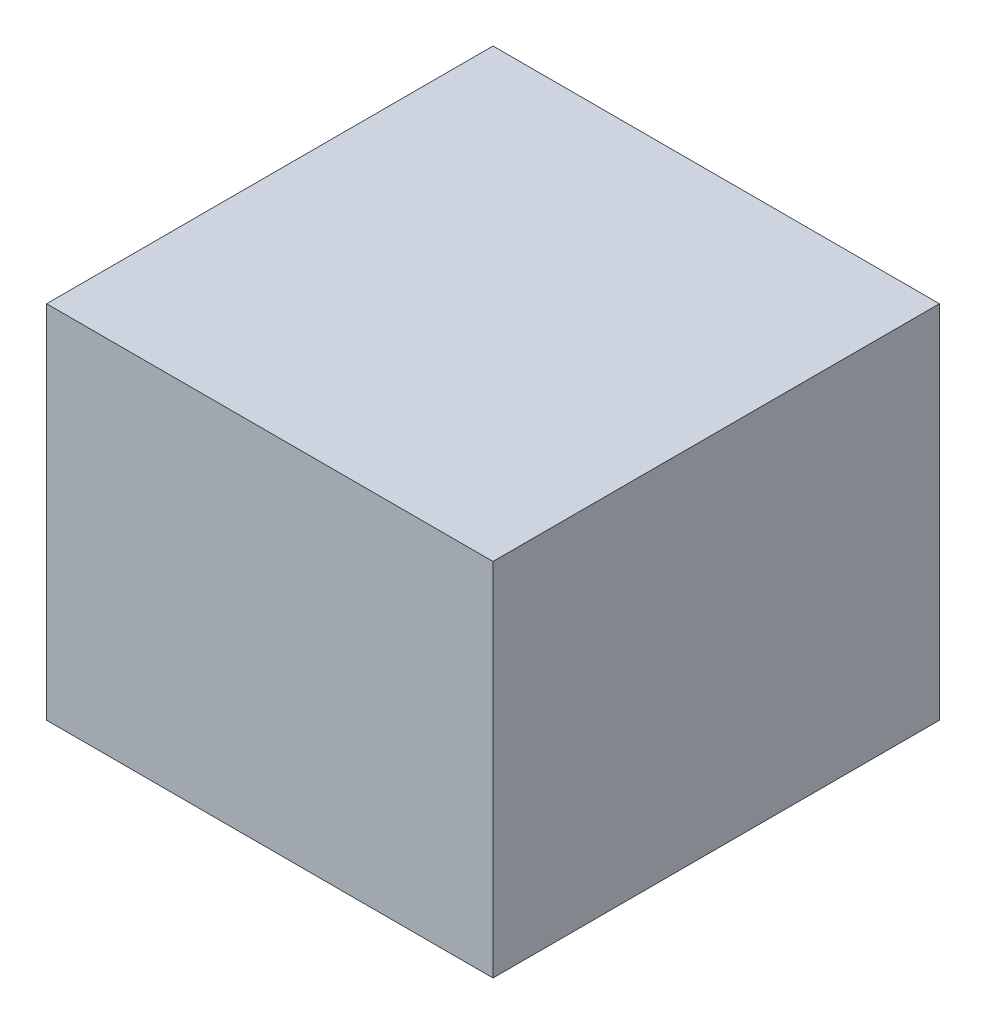
SolidWorks part; units mm, degrees
ref_plane "Front Plane" through (0, 0, 0) normal (0, 0, 1) x (1, 0, 0)
ref_plane "Top Plane" through (0, 0, 0) normal (0, 1, 0) x (1, 0, 0)
ref_plane "Right Plane" through (0, 0, 0) normal (1, 0, 0) x (0, 0, -1)
sketch "Sketch1" plane through (0, 0, 0) normal (0, 1, 0) x (1, 0, 0)
  line L1 (-24.75, -24.75) -> (24.75, -24.75)
  line L2 (-24.75, -24.75) -> (-24.75, 24.75)
  line L3 (-24.75, 24.75) -> (24.75, 24.75)
  line L4 (24.75, -24.75) -> (24.75, 24.75)
  line L5 (-24.75, -24.75) -> (24.75, 24.75) construction
  line L6 (-24.75, 24.75) -> (24.75, -24.75) construction
  point P0 (0, 0)
  dimension "D1" = 49.5
extrude "Boss-Extrude1" add sketch "Sketch1" along normal blind 40
